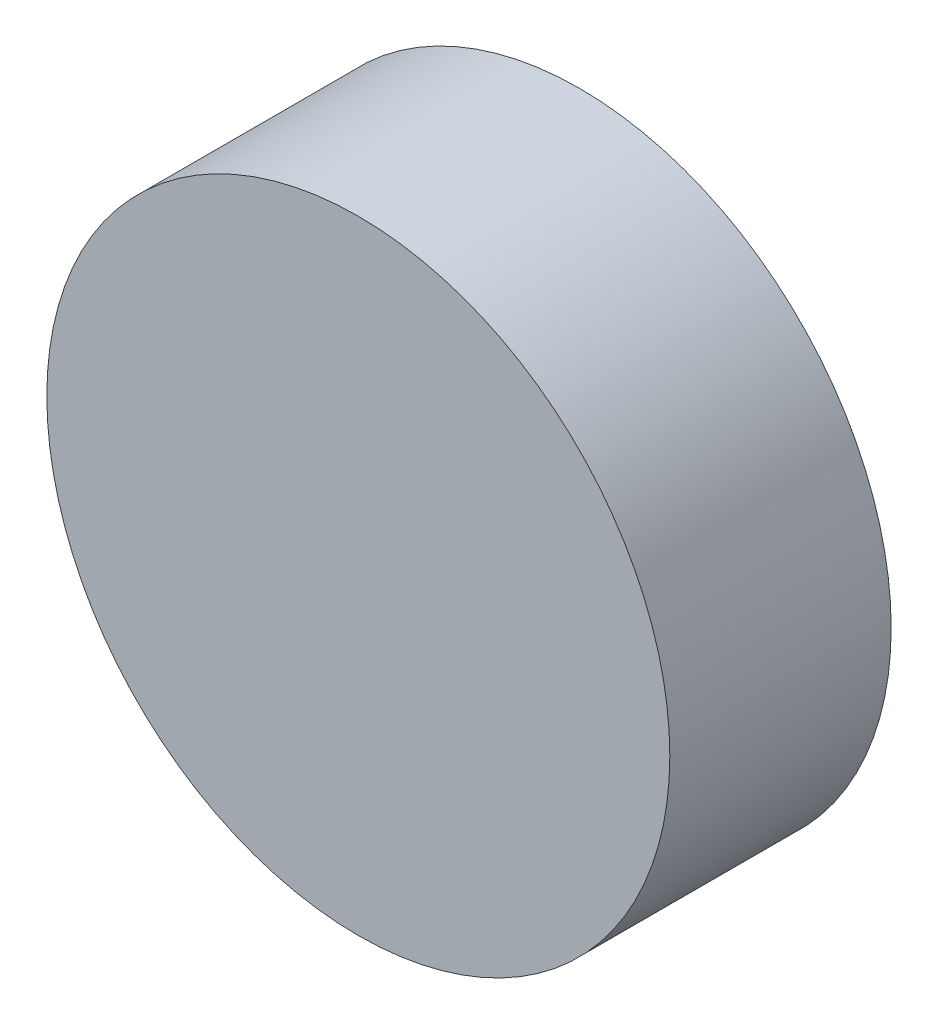
SolidWorks part; units mm, degrees
ref_plane "Front Plane" through (0, 0, 0) normal (0, 0, 1) x (1, 0, 0)
ref_plane "Top Plane" through (0, 0, 0) normal (0, 1, 0) x (1, 0, 0)
ref_plane "Right Plane" through (0, 0, 0) normal (1, 0, 0) x (0, 0, -1)
sketch "Sketch1" plane through (0, 0, 0) normal (0, 0, 1) x (1, 0, 0)
  circle A0 centre (0, 0) radius 71.4883
  dimension "D1" = 142.9766
extrude "Boss-Extrude1" add sketch "Sketch1" along normal blind 50.8
